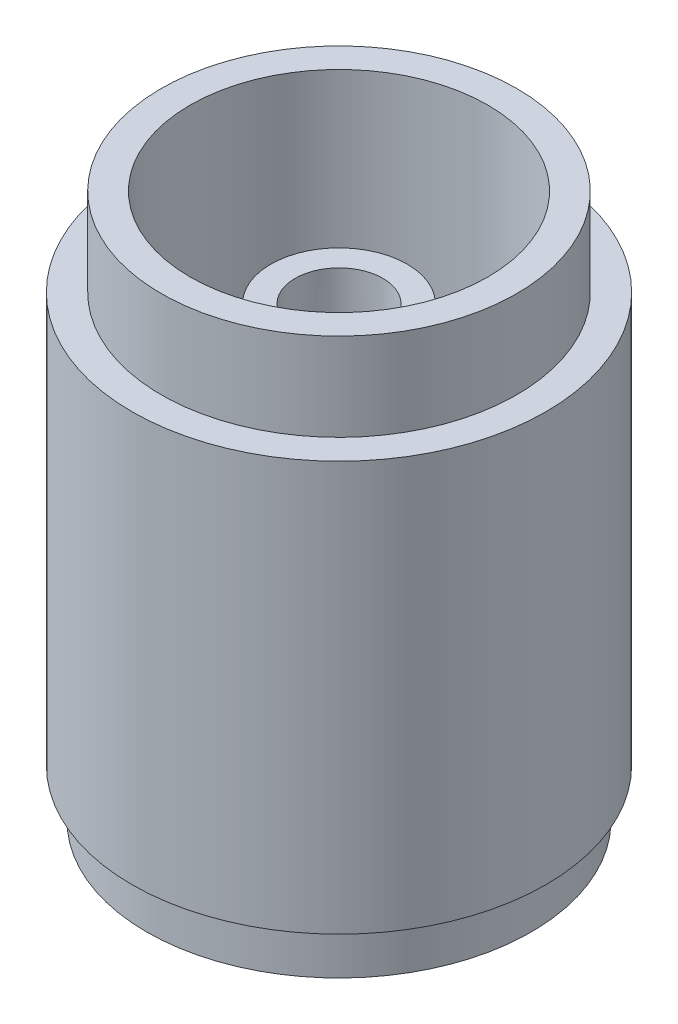
SolidWorks part; units mm, degrees
other "DetailItem1"
other "DetailItem2"
material "Pure Gold"
ref_plane "Front Plane" through (0, 0, 0) normal (0, 0, 1) x (1, 0, 0)
ref_plane "Top Plane" through (0, 0, 0) normal (0, 1, 0) x (1, 0, 0)
ref_plane "Right Plane" through (0, 0, 0) normal (1, 0, 0) x (0, 0, -1)
sketch "Sketch1" plane through (0, 0, 0) normal (0, 0, 1) x (1, 0, 0)
  line L0 (0, 0) -> (0, 91.6999) construction
  line L2 (-37.4832, 0) -> (-37.4832, 9.9138)
  line L3 (-37.4832, 9.9138) -> (-40.4832, 9.9138)
  line L4 (-40.4832, 9.9138) -> (-40.4832, 90)
  line L5 (-40.4832, 90) -> (-34.4832, 90)
  line L6 (-34.4832, 90) -> (-34.4832, 108)
  line L9 (-34.4832, 108) -> (-32.5683, 108)
  line L11 (-32.5683, 0) -> (-37.4832, 0)
  line L12 (0, 0) -> (-60, 0)
  line L13 (-32.5683, 9.9138) -> (0, 9.9138) construction
  line L14 (0, 9.9138) -> (0, 0)
  line L15 (-32.5683, 9.9138) -> (-19.5683, 9.9138) construction
  line L16 (-19.5683, 9.9138) -> (-19.5683, 19.9138) construction
  line L17 (-19.5683, 19.9138) -> (-32.5683, 19.9138) construction
  line L18 (-32.5683, 9.9138) -> (-19.5683, 9.9138)
  line L19 (-19.5683, 9.9138) -> (-19.5683, 19.9138)
  line L20 (-19.5683, 19.9138) -> (-32.5683, 27.6523)
  line L21 (-32.5683, 108) -> (-32.5683, 27.6523)
  line L22 (-32.5683, 9.9138) -> (-32.5683, 0)
  line L23 (0, 45.85) -> (-32.5683, 45.85) construction
  dimension "D1" = 3
  dimension "D2" = 6
revolve "Revolve-Thin2" add sketch "Sketch1" angle 360 about L0
sketch "Sketch2" plane through (0, 0, 0) normal (0, 0, 1) x (1, 0, 0)
  line L0 (0, 0) -> (0, 110) construction
  line L1 (36.4832, 110) -> (-36.4832, 110) construction
  line L6 (40.4832, 9.9138) -> (-40.4832, 9.9138) construction
  line L7 (-8, 9.9138) -> (-8, 19.5)
  line L8 (-8, 19.5) -> (-14.2066, 24.7396)
  line L9 (-14, 90) -> (-14.2066, 24.7396)
  line L11 (-34.4832, 90) -> (34.4832, 90) construction
  line L17 (-9, 89.9842) -> (-9.1992, 27.0559)
  line L18 (-3, 21.8224) -> (-9.1992, 27.0559)
  line L19 (-3, 21.8224) -> (-3, 9.9138)
  line L20 (-3, 9.9138) -> (-8, 9.9138)
  line L21 (-14, 90) -> (-9, 89.9842)
  line L25 (0, 14.9138) -> (-3, 14.9138) construction
  line L26 (0, 9.9138) -> (-8, 9.9138) construction
  line L27 (-3, 14.9138) -> (-3, 21.8224) construction
  dimension "D1" = 5
revolve "Revolve1" add sketch "Sketch2" angle 360 about L0
sketch "Sketch3" plane through (0, 0, 0) normal (0, 0, 1) x (1, 0, 0)
  line L2 (0, 53.5) -> (-42.4832, 53.5) construction
  line L3 (-42.4832, 92) -> (-42.4832, 7.9138) construction
  line L4 (0, 62.8381) -> (0, 44.6148) construction
  line L5 (0, 62.8381) -> (-27.9832, 62.8381) construction
  line L7 (-27.9832, 62.8381) -> (-27.9832, 44.6148) construction
  line L8 (-27.9832, 44.6148) -> (0, 44.6148) construction
  line L19 (-21.0438, 57.0381) -> (-23.9996, 50.3381) construction
  line L20 (-23.9996, 50.3381) -> (-18.0544, 50.3381) construction
  line L21 (-18.0544, 50.3381) -> (-18.0544, 57.0381) construction
  line L22 (-18.0544, 57.0381) -> (-21.0438, 57.0381) construction
  line L23 (-23.9996, 50.3381) -> (-18.0544, 50.3381) construction
  line L24 (-21.027, 50.3381) -> (-21.027, 57.0381)
  line L26 (-21.027, 50.3381) -> (-27.9832, 50.3381)
  line L27 (-32.5628, 44.6148) -> (0, 44.6148)
  line L28 (-32.5628, 44.6148) -> (-32.5628, 50.3381)
  line L29 (-32.5628, 50.3381) -> (-27.9832, 50.3381)
  line L31 (0, 44.6148) -> (0, 62.8381)
  line L32 (-32.5628, 62.8381) -> (-27.9832, 62.8381)
  line L33 (0, 62.8381) -> (-32.5628, 62.8381)
  line L34 (-32.5628, 57.0381) -> (-21.027, 57.0381)
  line L35 (0, 0) -> (0, 110) construction
  line L36 (32.5683, 0) -> (-32.5683, 0) construction
  line L37 (36.4832, 110) -> (-36.4832, 110) construction
  line L38 (-32.5628, 62.8381) -> (-32.5628, 57.0381)
  dimension "D2" = 42.4832
  dimension "D5" = 18.2233
revolve "Revolve4" add sketch "Sketch3" angle 360 about L35
